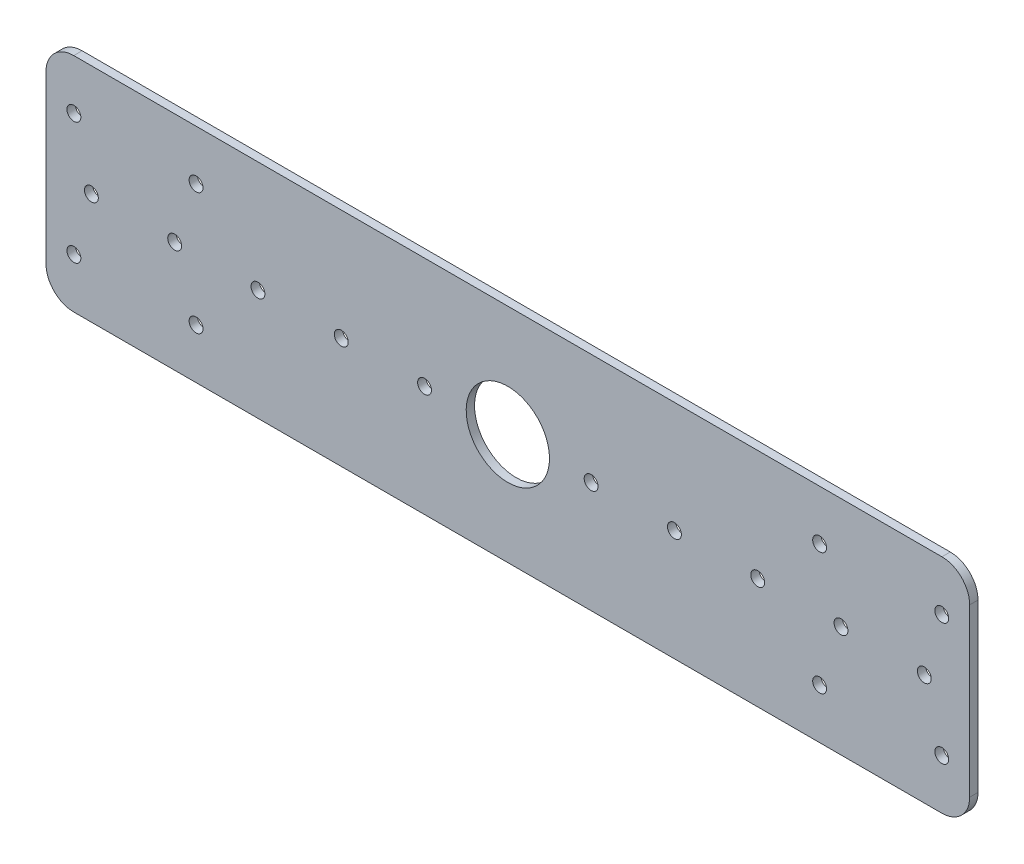
SolidWorks part; units mm, degrees
ref_plane "Front Plane" through (0, 0, 0) normal (0, 0, 1) x (1, 0, 0)
ref_plane "Top Plane" through (0, 0, 0) normal (0, 1, 0) x (1, 0, 0)
ref_plane "Right Plane" through (0, 0, 0) normal (1, 0, 0) x (0, 0, -1)
sketch "草图2" plane through (0, 0, 0) normal (0, 0, 1) x (1, 0, 0)
  line L1 (-248.8429, -104.4985) -> (83.8429, -104.4985)
  line L2 (-248.8429, -104.4985) -> (-248.8429, -175.4987)
  line L3 (-248.8429, -175.4987) -> (83.8429, -175.4987)
  line L4 (83.8429, -104.4985) -> (83.8429, -175.4987)
  line L5 (-248.8429, -104.4985) -> (83.8429, -175.4987) construction
  line L6 (-248.8429, -175.4987) -> (83.8429, -104.4985) construction
  line L7 (82.1109, -174.4987) -> (85.575, -176.4987) construction
  point P0 (-82.5, -139.9986)
  dimension "D1" = 71.0002
  dimension "D2" = 332.6859
extrude "凸台-拉伸1" add sketch "草图2" along normal blind 3
sketch "草图6" plane through (0, 0, 3) normal (0, 0, 1) x (1, 0, 0)
  circle A0 centre (-82.5, -139.9986) radius 15
  dimension "D1" = 30
extrude "切除-拉伸1" cut sketch "草图6" against normal blind 10
sketch "草图7" plane through (0, 0, 0) normal (0, 0, -1) x (-1, 0, 0)
  circle A0 centre (238.8, -117.9986) radius 2.5
  circle A1 centre (194.8, -117.9986) radius 2.5
  circle A2 centre (194.8, -161.9986) radius 2.5
  circle A3 centre (238.8, -161.9986) radius 2.5
  circle A4 centre (-73.8, -161.9986) radius 2.5
  circle A5 centre (-29.8, -161.9986) radius 2.5
  circle A6 centre (-29.8, -117.9986) radius 2.5
  circle A7 centre (-73.8, -117.9986) radius 2.5
  dimension "D1" = 5
  dimension "D2" = 5
  dimension "D3" = 5
  dimension "D4" = 5
extrude "切除-拉伸2" cut sketch "草图7" against normal blind 10
sketch "草图8" plane through (0, 0, 3) normal (0, 0, 1) x (1, 0, 0)
  line L0 (83.8429, -175.4987) -> (83.8429, -104.4985) construction
  line L1 (-248.8429, -179.9986) -> (83.8429, -179.9986)
  line L2 (-248.8429, -179.9986) -> (-248.8429, -99.9986)
  line L3 (-248.8429, -99.9986) -> (83.8429, -99.9986)
  line L4 (83.8429, -179.9986) -> (83.8429, -99.9986)
  line L5 (-248.8429, -179.9986) -> (83.8429, -99.9986) construction
  line L6 (-248.8429, -99.9986) -> (83.8429, -179.9986) construction
  point P0 (-82.5, -139.9986)
  line M11 (83.8429, -104.4985) -> (-248.8429, -104.4985)
  line M13 (-248.8429, -175.4987) -> (83.8429, -175.4987)
  dimension "D1" = 80
extrude "凸台-拉伸2" add sketch "草图8" against normal blind 3 contours L4 L3 L2 M11 | L1 L4 L2 M13
fillet "圆角1" radius 10 4 edges at (83.8429, -179.9986, 1.5) (83.8429, -99.9986, 1.5) (-248.8429, -179.9986, 1.5) (-248.8429, -99.9986, 1.5)
sketch "草图9" plane through (0, 0, 0) normal (0, 0, -1) x (-1, 0, 0)
  circle A0 centre (82.5, -139.9986) radius 2.5
  circle A1 centre (52.5, -139.9986) radius 2.5
  circle A2 centre (22.5, -139.9986) radius 2.5
  circle A3 centre (-7.5, -139.9986) radius 2.5
  circle A4 centre (-37.5, -139.9986) radius 2.5
  circle A5 centre (-67.5, -139.9986) radius 2.5
  circle A6 centre (-97.5, -139.9986) radius 2.5
  circle A7 centre (-127.5, -139.9986) radius 2.5
  circle A8 centre (82.5, -139.9986) radius 2.5
  circle A9 centre (52.5, -139.9986) radius 2.5
  circle A10 centre (22.5, -139.9986) radius 2.5
  circle A11 centre (-7.5, -139.9986) radius 2.5
  circle A12 centre (-37.5, -139.9986) radius 2.5
  circle A13 centre (-67.5, -139.9986) radius 2.5
  circle A14 centre (-97.5, -139.9986) radius 2.5
  circle A15 centre (112.5, -139.9986) radius 2.5
  circle A16 centre (82.5, -139.9986) radius 2.5
  circle A17 centre (52.5, -139.9986) radius 2.5
  circle A18 centre (22.5, -139.9986) radius 2.5
  circle A19 centre (-7.5, -139.9986) radius 2.5
  circle A20 centre (-37.5, -139.9986) radius 2.5
  circle A21 centre (-67.5, -139.9986) radius 2.5
  circle A22 centre (142.5, -139.9986) radius 2.5
  circle A23 centre (112.5, -139.9986) radius 2.5
  circle A24 centre (82.5, -139.9986) radius 2.5
  circle A25 centre (52.5, -139.9986) radius 2.5
  circle A26 centre (22.5, -139.9986) radius 2.5
  circle A27 centre (-7.5, -139.9986) radius 2.5
  circle A28 centre (-37.5, -139.9986) radius 2.5
  circle A29 centre (172.5, -139.9986) radius 2.5
  circle A30 centre (142.5, -139.9986) radius 2.5
  circle A31 centre (112.5, -139.9986) radius 2.5
  circle A32 centre (82.5, -139.9986) radius 2.5
  circle A33 centre (52.5, -139.9986) radius 2.5
  circle A34 centre (22.5, -139.9986) radius 2.5
  circle A35 centre (-7.5, -139.9986) radius 2.5
  circle A36 centre (202.5, -139.9986) radius 2.5
  circle A37 centre (172.5, -139.9986) radius 2.5
  circle A38 centre (142.5, -139.9986) radius 2.5
  circle A39 centre (112.5, -139.9986) radius 2.5
  circle A40 centre (82.5, -139.9986) radius 2.5
  circle A41 centre (52.5, -139.9986) radius 2.5
  circle A42 centre (22.5, -139.9986) radius 2.5
  circle A43 centre (232.5, -139.9986) radius 2.5
  circle A44 centre (202.5, -139.9986) radius 2.5
  circle A45 centre (172.5, -139.9986) radius 2.5
  circle A46 centre (142.5, -139.9986) radius 2.5
  circle A47 centre (112.5, -139.9986) radius 2.5
  circle A48 centre (82.5, -139.9986) radius 2.5
  circle A49 centre (52.5, -139.9986) radius 2.5
  circle A50 centre (262.5, -139.9986) radius 2.5
  circle A51 centre (232.5, -139.9986) radius 2.5
  circle A52 centre (202.5, -139.9986) radius 2.5
  circle A53 centre (172.5, -139.9986) radius 2.5
  circle A54 centre (142.5, -139.9986) radius 2.5
  circle A55 centre (112.5, -139.9986) radius 2.5
  circle A56 centre (82.5, -139.9986) radius 2.5
  circle A57 centre (112.5, -139.9986) radius 2.5
  circle A58 centre (142.5, -139.9986) radius 2.5
  circle A59 centre (172.5, -139.9986) radius 2.5
  circle A60 centre (202.5, -139.9986) radius 2.5
  circle A61 centre (232.5, -139.9986) radius 2.5
  circle A62 centre (262.5, -139.9986) radius 2.5
  circle A63 centre (292.5, -139.9986) radius 2.5
  dimension "D1" = 5
  dimension "D2" = 8
  dimension "D3" = 8
extrude "切除-拉伸3" cut sketch "草图9" against normal through all contours A36 | A29 | A22 | A15 | A1 | A2 | A3 | A4 | A5 | A43
